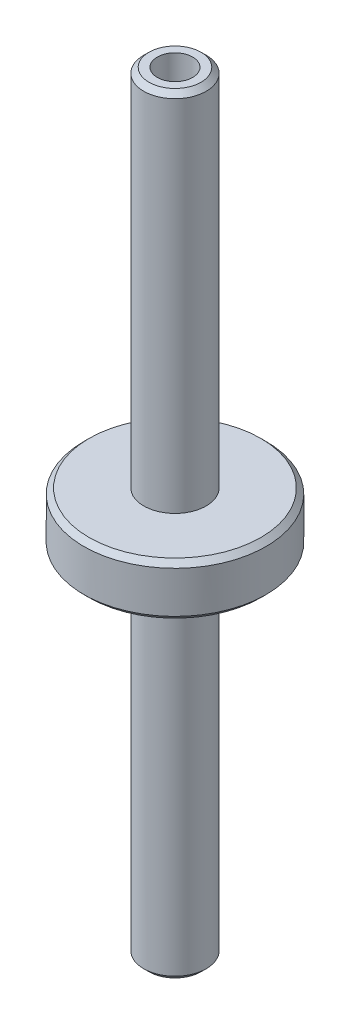
SolidWorks part; units mm, degrees
ref_plane "Front Plane" through (0, 0, 0) normal (0, 0, 1) x (1, 0, 0)
ref_plane "Top Plane" through (0, 0, 0) normal (0, 1, 0) x (1, 0, 0)
ref_plane "Right Plane" through (0, 0, 0) normal (1, 0, 0) x (0, 0, -1)
sketch "Sketch1" plane through (0, 0, 0) normal (0, 0, 1) x (1, 0, 0)
  line L0 (0, 34.4277) -> (0, -49965.5723) construction
  line L1 (0, -55) -> (0, 55) construction
  line L2 (0, 70) -> (0, -78)
  line L3 (0, -78) -> (-6, -78)
  line L4 (-6, -78) -> (-6, -10)
  line L5 (-6, -10) -> (-17.5, -10)
  line L6 (-17.5, -10) -> (-17.5, 0)
  line L7 (-17.5, 0) -> (-6, 0)
  line L8 (-6, 0) -> (-6, 70)
  line L9 (-6, 70) -> (0, 70)
  line L12 (55, 0) -> (-55, 0) construction
  dimension "D1" = 70
  dimension "D2" = 148
  dimension "D3" = 10
  dimension "D4" = 12
  dimension "D5" = 35
revolve "Revolve1" add sketch "Sketch1" angle 360 about L0
chamfer "Chamfer1" distance 1 angle 45 4 edges at (-6, -78, 0) (-17.5, 0, 0) (-17.5, -10, 0) (-6, 70, 0)
hole_wizard "Trou taraudé M81" positions "Sketch2" profile "Sketch3" tap size "M8" standard "ISO"
sketch "Sketch2" plane through (0, 70, 0) normal (0, 1, 0) x (1, 0, 0)
  line L0 (0, -19.25) -> (0, 19.25) construction
  line L1 (-19.25, 0) -> (19.25, 0) construction
  point P0 (0, 0)
cosmetic thread "Hole Thread1" parameters "D1"=15, "D2"=8
sketch "Sketch3" plane through (0, 70, 0) normal (1, 0, 0) x (0, 0, 1)
  line L0 (0, 0) -> (0, 24.0429)
  line L1 (0, 24.0429) -> (3.4, 22)
  line L2 (3.4, 22) -> (3.4, 0)
  line L5 (3.4, 0) -> (0, 0)
  line L10 (0, 24.0429) -> (-3.4, 22) construction
  line L11 (0, -6.35) -> (0, 107.95) construction
  dimension "Tap Drill Dia." = 6.8
  dimension "Tap Drill Depth" = 22
  dimension "Drill Angle" = 118
